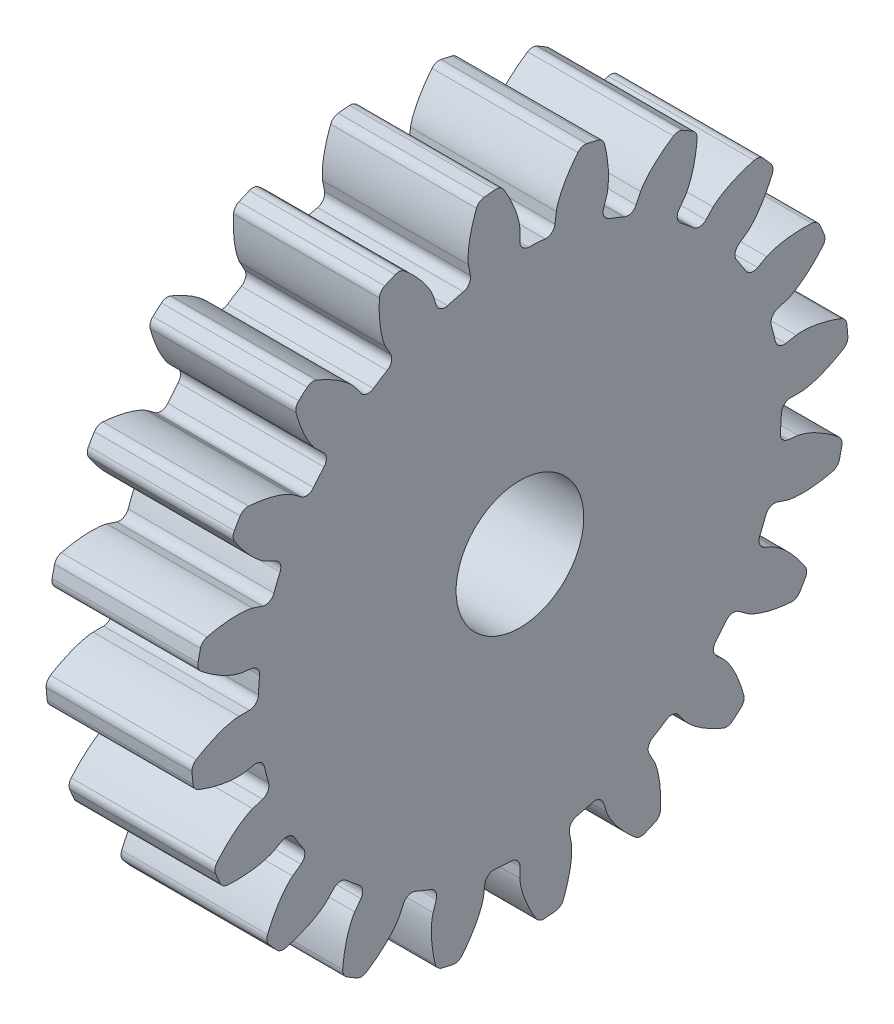
SolidWorks part; units mm, degrees
ref_plane "Front Plane" through (0, 0, 0) normal (0, 0, 1) x (1, 0, 0)
ref_plane "Top Plane" through (0, 0, 0) normal (0, 1, 0) x (1, 0, 0)
ref_plane "Right Plane" through (0, 0, 0) normal (1, 0, 0) x (0, 0, -1)
ref_axis "Axis1" through (88.99, 0, 0) along (-1, 0, 0)
sketch "Sketch2" plane through (0, 0, 0) normal (1, 0, 0) x (0, -1, 0)
  circle A0 centre (0, 0) radius 9.02
  circle A1 centre (0, 0) radius 1.75
  dimension "D1" = 18.04
  dimension "D2" = 3.5
extrude "Boss-Extrude1" add sketch "Sketch2" along normal mid plane 4
sketch "Sketch3" plane through (2, 0, 0) normal (1, 0, 0) x (0, 0, -1)
  line L0 (0, 0) -> (-7.7055, 0) construction
  line L1 (0, 0) -> (-8.1992, -0.1109) construction
  line L2 (0, 0) -> (-9.0009, 0.586) construction
  line L3 (7.175, 0) -> (-7.7055, 0)
  line L4 (-7.1598, 0.4661) -> (-9.0009, 0.586)
  arc A0 (-8.1827, 0.5327) -> (-8.1992, -0.1109) centre (0, 0) ccw construction
  arc A1 (-7.7055, 0) -> (-7.7048, -0.1042) centre (0, 0) ccw construction
  arc A2 (-7.1598, 0.4661) -> (-7.175, 0) centre (0, 0) ccw
  circle A3 centre (0, 0) radius 9.02 construction
  arc A4 (-7.7055, 0) -> (-7.6892, 0.5006) centre (0, 0) cw construction
  arc A5 (-9.0009, 0.586) -> (-9.0048, -0.5238) centre (0, 0) ccw
  arc A6 (-7.1743, -0.0971) -> (7.175, 0) centre (0, 0) ccw construction
  arc A7 (-7.7048, -0.1042) -> (-7.6892, 0.5006) centre (0, 0) ccw construction
  arc A8 (-8.1992, -0.1109) -> (-8.1827, 0.5327) centre (0, 0) ccw construction
  arc A9 (7.175, 0) -> (-7.1598, 0.4661) centre (0, 0) ccw construction
  arc A10 (-7.6892, 0.5006) -> (-7.7055, 0) centre (0, 0) ccw construction
  arc A11 (-7.175, 0) -> (-7.1743, -0.0971) centre (0, 0) ccw construction
  spline S0 degree 4 poles (-7.7055, 0) (-7.7112, 0) (-7.7272, -0.0004) (-7.7573, -0.0026) (-7.8064, -0.0082) (-7.8686, -0.0184) (-7.9485, -0.0352) (-8.0418, -0.0594) (-8.1434, -0.0906) (-8.2525, -0.1295) (-8.3602, -0.1726) (-8.4663, -0.2196) (-8.5707, -0.2701) (-8.6955, -0.3353) (-8.8429, -0.4192) (-9.0113, -0.5255) (-9.1977, -0.6555) (-9.382, -0.7978) (-9.5588, -0.9459) (-9.7315, -1.1044) (-9.8945, -1.2639) (-10.0573, -1.4383) (-10.2042, -1.6036) (-10.3613, -1.7979) (-10.4859, -1.9574) (-10.6416, -2.177) (-10.7311, -2.3094) (-10.8327, -2.4674) (-10.8762, -2.5391) (-10.903, -2.5833) knots 0 0 0 0 0 0.005377 0.015084 0.028532 0.04661 0.064855 0.092111 0.119476 0.146842 0.174209 0.201575 0.228941 0.256307 0.307035 0.361767 0.4165 0.471232 0.525964 0.580697 0.635429 0.690161 0.744894 0.799626 0.854358 0.909091 0.954545 1 1 1 1 1 construction
  spline S1 degree 4 poles (-7.7055, 0) (-7.7112, 0) (-7.7272, -0.0004) (-7.7573, -0.0026) (-7.8064, -0.0082) (-7.8686, -0.0184) (-7.9485, -0.0352) (-8.0418, -0.0594) (-8.1434, -0.0906) (-8.2525, -0.1295) (-8.3602, -0.1726) (-8.4663, -0.2196) (-8.5707, -0.2701) (-8.6955, -0.3353) (-8.8429, -0.4192) (-9.0113, -0.5255) (-9.1977, -0.6555) (-9.382, -0.7978) (-9.5588, -0.9459) (-9.7315, -1.1044) (-9.8945, -1.2639) (-10.0573, -1.4383) (-10.2042, -1.6036) (-10.3613, -1.7979) (-10.4859, -1.9574) (-10.6079, -2.1294) (-10.6662, -2.2141) (-10.6957, -2.2579) knots 0 0 0 0 0 0.005377 0.015084 0.028532 0.04661 0.064855 0.092111 0.119476 0.146842 0.174209 0.201575 0.228941 0.256307 0.307035 0.361767 0.4165 0.471232 0.525964 0.580697 0.635429 0.690161 0.744894 0.799626 0.854358 0.909091 0.909091 0.909091 0.909091 0.909091
  circle M1 centre (0, 0) radius 9.02
  dimension "D1" = 16.4
  dimension "D2" = 15.411
  dimension "D3" = 14.35
  dimension "D4" = 4.5
extrude "Cut-Extrude1" cut sketch "Sketch3" against normal through all contours S1 A0 L4 M1 | S1 A1 L4 A0 | A2 L4 A1 L3
ref_plane "Plane1" through (0, 0, 0) normal (0, 0.9979, -0.065) x (1, 0, 0)
mirror "Mirror2" about plane through (0, 0, 0) normal (0, 0.9979, -0.065) of "Cut-Extrude1"
pattern_circular "CirPattern9" count 20 over 360 about axis through (88.99, 0, 0) along (-1, 0, 0) of "Mirror2", "Cut-Extrude1"
fillet "Fillet7" radius 0.25 80 edges at (0, -2.2172, 6.8238) (0, -4.2174, 5.8047) (0, -5.8047, 4.2174) (0, -6.8238, 2.2172) (0, -7.175, 0) (0, -6.8238, -2.2172) (0, -5.8047, -4.2174) (0, -4.2174, -5.8047) (0, -2.2172, -6.8238) (0, 0, -7.175) (0, 2.2172, -6.8238) (0, 4.2174, -5.8047) (0, 5.8047, -4.2174) (0, 6.8238, -2.2172) (0, 7.175, 0) (0, 6.8238, 2.2172) (0, 5.8047, 4.2174) (0, 4.2174, 5.8047) (0, 2.2172, 6.8238) (0, -1.3137, 7.0537) (0, -3.4291, 6.3025) (0, -5.2089, 4.9344) (0, -6.4787, 3.0833) (0, -7.1144, 0.9303) (0, -7.0537, -1.3137) (0, -6.3025, -3.4291) (0, -4.9344, -5.2089) (0, -3.0833, -6.4787) (0, -0.9303, -7.1144) (0, 1.3137, -7.0537) (0, 3.4291, -6.3025) (0, 5.2089, -4.9344) (0, 7.1144, -0.9303) (0, 7.0537, 1.3137) (0, 6.3025, 3.4291) (0, 4.9344, 5.2089) (0, 3.0833, 6.4787) (0, 6.4787, -3.0833) (0, 0.9303, 7.1144) (0, 0, 7.175) (0, -4.8691, -7.5929) (0, -4.3425, -7.9059) (0, -2.2845, -8.7259) (0, -1.6869, -8.8609) (0, 0.5238, -9.0048) (0, 1.1338, -8.9485) (0, 3.2808, -8.4022) (0, 3.8435, -8.1601) (0, 5.7166, -6.9772) (0, 6.177, -6.573) (0, 7.5929, -4.8691) (0, 7.9059, -4.3425) (0, 8.7259, -2.2845) (0, 8.8609, -1.6869) (0, 9.0048, 0.5238) (0, 8.9485, 1.1338) (0, 8.4022, 3.2808) (0, 8.1601, 3.8435) (0, 6.9772, 5.7166) (0, 6.573, 6.177) (0, 4.8691, 7.5929) (0, 4.3425, 7.9059) (0, 2.2845, 8.7259) (0, 1.6869, 8.8609) (0, -0.5238, 9.0048) (0, -1.1338, 8.9485) (0, -3.2808, 8.4022) (0, -3.8435, 8.1601) (0, -6.177, 6.573) (0, -7.5929, 4.8691) (0, -7.9059, 4.3425) (0, -8.7259, 2.2845) (0, -8.8609, 1.6869) (0, -9.0048, -0.5238) (0, -8.9485, -1.1338) (0, -8.4022, -3.2808) (0, -8.1601, -3.8435) (0, -6.9772, -5.7166) (0, -6.573, -6.177) (0, -5.7166, 6.9772)
equation "\"d\"= 16.4'Pitch Circle Diameter"
equation "\"t\"= 20'Number of Teeth"
equation "\"phi\"= 20deg'Pressure Angle"
equation "\"m\"= \"d\" / \"t\"'Module"
equation "\"a\"= \"m\"'Addendum"
equation "\"b\"= 1.25 * \"m\"'Dedendum"
equation "\"c\"= \"b\" - \"a\"'Clearence"
equation "\"db\"= \"d\" * cos ( \"phi\" )'Base Circle Diameter"
equation "\"D1@Sketch2\"=\"d\"+2*\"a\""
equation "\"D1@Sketch3\"=\"d\""
equation "\"D2@Sketch3\"=\"db\""
equation "\"D3@Sketch3\"=\"d\"-2*\"b\""
equation "\"D4@Sketch3\"=360/(4*\"t\")"
equation "\"D1@CirPattern9\"=\"t\""
